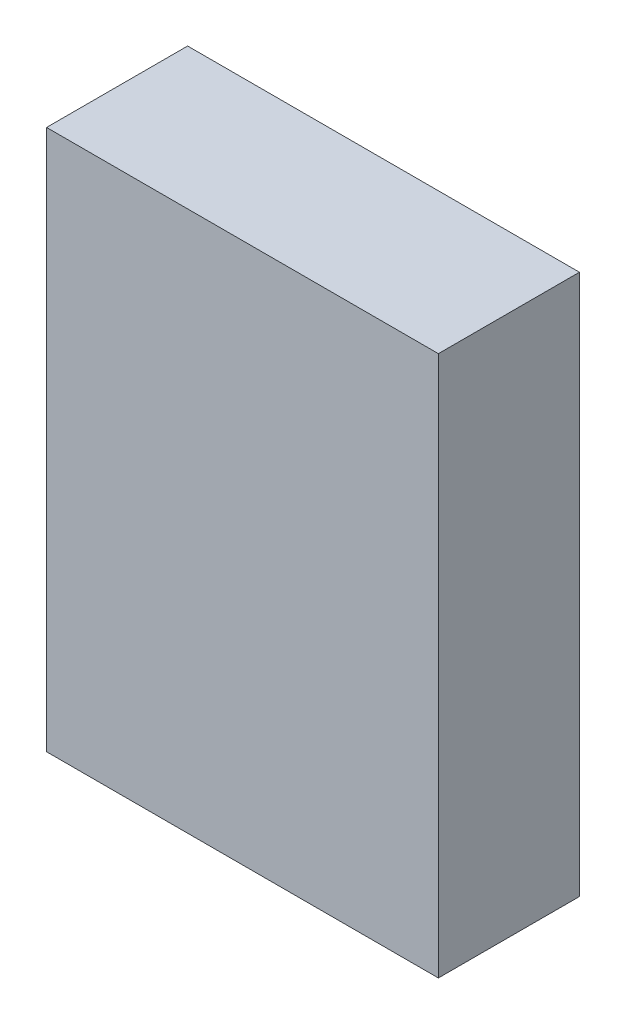
SolidWorks part; units mm, degrees
ref_plane "Front Plane" through (0, 0, 0) normal (0, 0, 1) x (1, 0, 0)
ref_plane "Top Plane" through (0, 0, 0) normal (0, 1, 0) x (1, 0, 0)
ref_plane "Right Plane" through (0, 0, 0) normal (1, 0, 0) x (0, 0, -1)
sketch "Sketch1" plane through (0, 0, 0) normal (0, 0, 1) x (1, 0, 0)
  line L1 (0, 0) -> (50, 0)
  line L2 (0, 0) -> (0, 69)
  line L3 (0, 69) -> (50, 69)
  line L4 (50, 0) -> (50, 69)
  dimension "D1" = 69
  dimension "D2" = 50
extrude "Boss-Extrude1" add sketch "Sketch1" along normal blind 18
